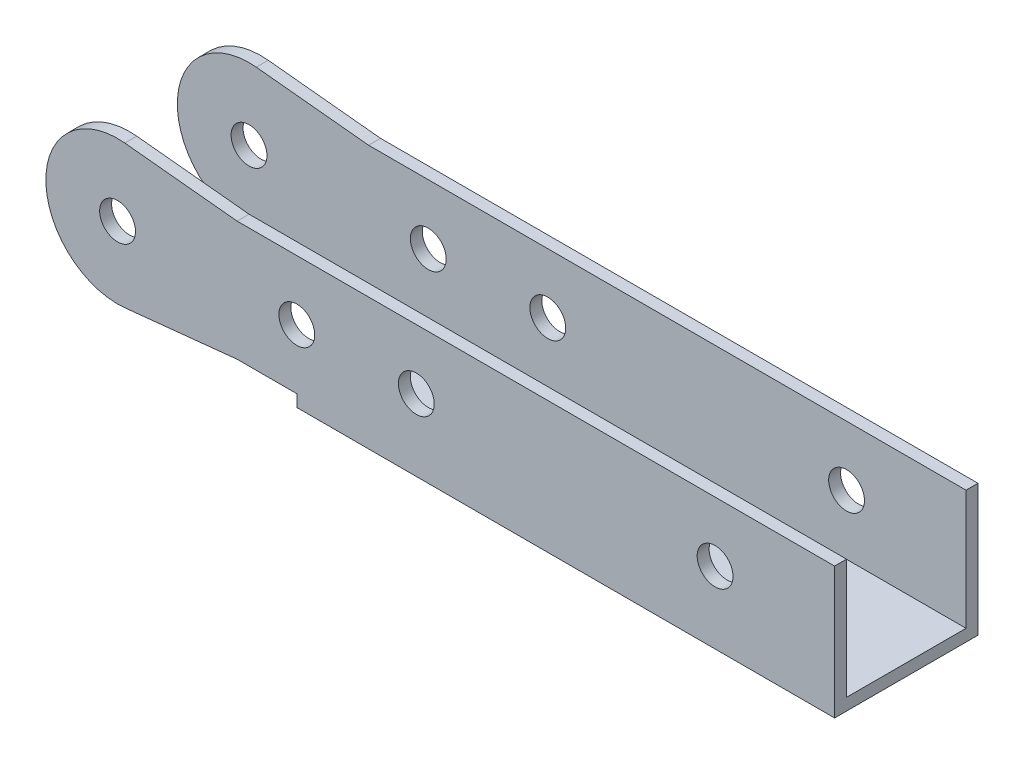
SolidWorks part; units mm, degrees
ref_plane "前视基准面" through (0, 0, 0) normal (0, 0, 1) x (1, 0, 0)
ref_plane "上视基准面" through (0, 0, 0) normal (0, 1, 0) x (1, 0, 0)
ref_plane "右视基准面" through (0, 0, 0) normal (1, 0, 0) x (0, 0, -1)
sketch "草图1" plane through (0, 0, 0) normal (0, 0, 1) x (1, 0, 0)
  line L0 (23.2, 8.0104) -> (-26.8, 8.0104)
  line L1 (-26.8, -2) -> (23.2, -2)
  line L2 (-60.7008, 3) -> (100.6682, 3) construction
  line L3 (23.2, 8.0104) -> (23.2, -2)
  line L6 (-26.8, 8.0104) -> (-36.1907, 8.969)
  line L7 (-26.8, -2) -> (-36.1842, -2.9683)
  circle A0 centre (-36.8, 3) radius 1.5
  arc A1 (-36.1907, 8.969) -> (-36.1842, -2.9683) centre (-36.8, 3) ccw
  circle A2 centre (-21.8, 3) radius 1.5
  circle A3 centre (-11.8, 3) radius 1.5
  circle A4 centre (13.2, 3) radius 1.5
  dimension "D1" = 5
  dimension "D4" = 15
  dimension "D5" = 3
  dimension "D6" = 12
  dimension "D2" = 3
  dimension "D3" = 25
  dimension "D7" = 3
  dimension "D8" = 10
  dimension "D9" = 10
  dimension "D10" = 50
  dimension "D12" = 50
ref_plane "基准面1" through (0, -2, 0) normal (0, -1, 0) x (1, 0, 0)
ref_plane "基准面2" through (0, 0, 10) normal (0, 0, 1) x (1, 0, 0)
sketch "草图3" plane through (0, 0, 10) normal (0, 0, 1) x (1, 0, 0)
  line L5 (-26.8, 8.0104) -> (-36.1907, 8.969)
  line L6 (23.2, 8.0104) -> (-26.8, 8.0104)
  line L7 (23.2, -2) -> (23.2, 8.0104)
  line L8 (-26.8, -2) -> (23.2, -2)
  line L9 (-36.1842, -2.9683) -> (-26.8, -2)
  line L10 (-26.8, 8.0104) -> (-36.1907, 8.969)
  line L11 (23.2, 8.0104) -> (-26.8, 8.0104)
  line L12 (23.2, -2) -> (23.2, 8.0104)
  line L13 (-26.8, -2) -> (23.2, -2)
  line L14 (-36.1842, -2.9683) -> (-26.8, -2)
  circle A1 centre (13.2, 3) radius 1.5
  circle A2 centre (13.2, 3) radius 1.5
  circle A3 centre (-11.8, 3) radius 1.5
  circle A4 centre (-11.8, 3) radius 1.5
  circle A5 centre (-21.8, 3) radius 1.5
  circle A6 centre (-21.8, 3) radius 1.5
  circle A7 centre (-36.8, 3) radius 1.5
  circle A8 centre (-36.8, 3) radius 1.5
  arc A9 (-36.1907, 8.969) -> (-36.1842, -2.9683) centre (-36.8, 3) ccw
  arc A10 (-36.1907, 8.969) -> (-36.1842, -2.9683) centre (-36.8, 3) ccw
  dimension "D1" = 0
  dimension "D2" = 0
  dimension "D3" = 0
  dimension "D4" = 0
  dimension "D5" = 0
extrude "凸台-拉伸1" add sketch "草图3" along normal blind 1
extrude "凸台-拉伸2" add sketch "草图1" against normal blind 1 separate body
sketch "草图4" plane through (0, -2, 0) normal (0, -1, 0) x (1, 0, 0)
  line L0 (23.2, 11) -> (23.2, -1)
  line L1 (23.2, -1) -> (-21.8, -1)
  line L2 (-26.8, -1) -> (23.2, -1) construction
  line L3 (-21.8, -1) -> (-21.8, 11)
  line L4 (-26.8, 11) -> (23.2, 11) construction
  line L5 (-21.8, 11) -> (23.2, 11)
  line L6 (-36.8, 6.7279) -> (-36.8, -2.3916) construction
  line L7 (-36.8, 11) -> (-36.8, 10) construction
  dimension "D1" = 15
extrude "凸台-拉伸3" add sketch "草图4" along normal blind 1
